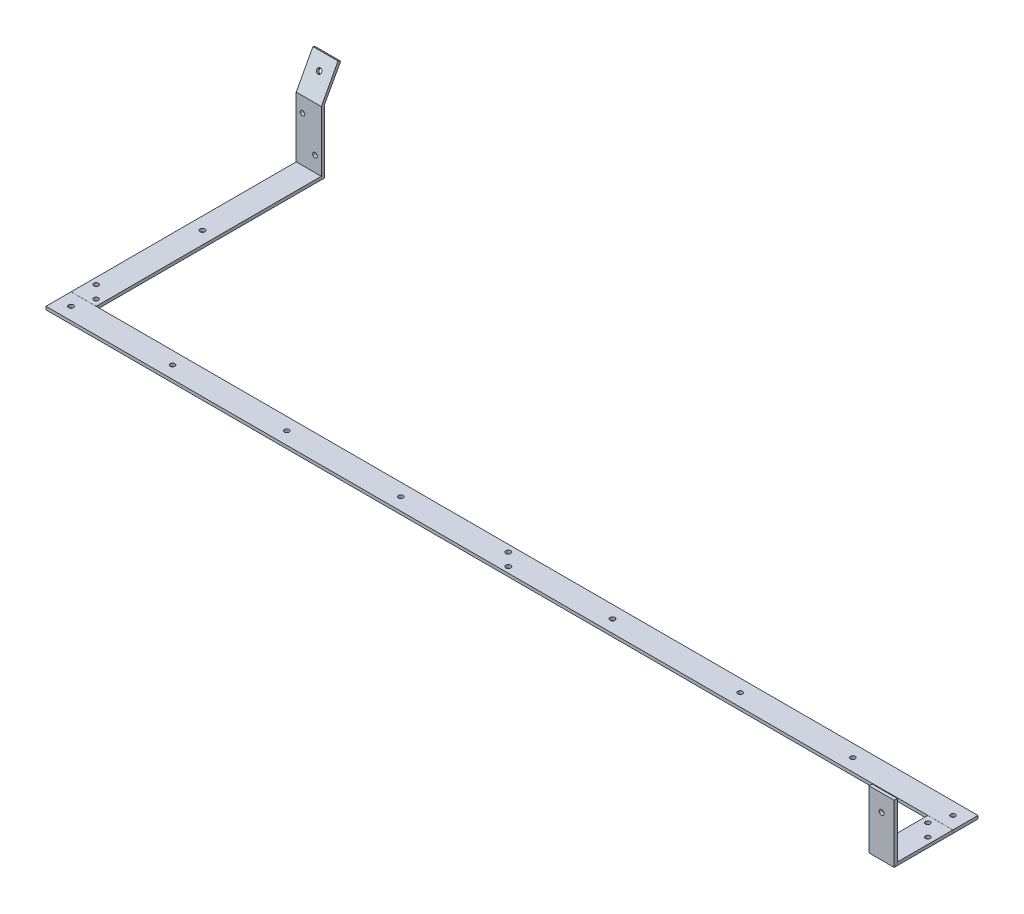
SolidWorks part; units mm, degrees
ref_plane "Alzado" through (0, 0, 0) normal (0, 0, 1) x (1, 0, 0)
ref_plane "Planta" through (0, 0, 0) normal (0, 1, 0) x (1, 0, 0)
ref_plane "Vista lateral" through (0, 0, 0) normal (1, 0, 0) x (0, 0, -1)
sketch "Croquis2" plane through (0, 0, 0) normal (0, 0, 1) x (1, 0, 0)
  line L1 (-25.4, 64.345) -> (25.4, 64.345)
  line L2 (-25.4, 64.345) -> (-25.4, -64.345)
  line L3 (-25.4, -64.345) -> (25.4, -64.345)
  line L4 (25.4, 64.345) -> (25.4, -64.345)
  line L5 (-25.4, 64.345) -> (25.4, -64.345) construction
  line L6 (-25.4, -64.345) -> (25.4, 64.345) construction
  point P0 (0, 0)
  dimension "D1" = 128.69
  dimension "D2" = 50.8
extrude "Saliente-Extruir1" add sketch "Croquis2" along normal blind 6.31
sketch "Croquis3" plane through (0, 0, 6.31) normal (0, 0, 1) x (1, 0, 0)
  line L1 (-25.4, -58.035) -> (25.4, -58.035)
  line L2 (-25.4, -58.035) -> (-25.4, -64.345)
  line L3 (-25.4, -64.345) -> (25.4, -64.345)
  line L4 (25.4, -58.035) -> (25.4, -64.345)
  line L5 (-25.4, -58.035) -> (25.4, -64.345) construction
  line L6 (-25.4, -64.345) -> (25.4, -58.035) construction
  point P0 (0, -61.19)
  dimension "D1" = 6.31
  dimension "D2" = 50.8
extrude "Saliente-Extruir2" add sketch "Croquis3" along normal blind 507.13
sketch "Croquis4" plane through (25.4, 0, 0) normal (1, 0, 0) x (0, 0, -1)
  line L1 (-462.64, -64.345) -> (-513.44, -64.345)
  line L2 (-462.64, -64.345) -> (-462.64, -58.035)
  line L3 (-462.64, -58.035) -> (-513.44, -58.035)
  line L4 (-513.44, -64.345) -> (-513.44, -58.035)
  line L5 (-462.64, -64.345) -> (-513.44, -58.035) construction
  line L6 (-462.64, -58.035) -> (-513.44, -64.345) construction
  point P0 (-488.04, -61.19)
  dimension "D1" = 50.8
extrude "Saliente-Extruir3" add sketch "Croquis4" along normal blind 1787.3
sketch "Croquis9" plane through (0, 0, 513.44) normal (0, 0, 1) x (1, 0, 0)
  line L0 (1812.7, -58.035) -> (-25.4, -58.035) construction
  line L1 (1761.9, -58.035) -> (1812.7, -58.035)
  line L2 (1761.9, -58.035) -> (1761.9, -64.345)
  line L3 (1761.9, -64.345) -> (1812.7, -64.345)
  line L4 (1812.7, -58.035) -> (1812.7, -64.345)
  line L5 (1761.9, -58.035) -> (1812.7, -64.345) construction
  line L6 (1761.9, -64.345) -> (1812.7, -58.035) construction
  point P0 (1787.3, -61.19)
  dimension "D1" = 50.8
sketch3d "Croquis3D3"
  line L0 (1787.3, -61.19, 513.44) -> (1787.3, -61.19, 629.44)
  line L1 (1787.3, -61.19, 629.44) -> (1787.3, 63.52, 629.44)
  line L2 (1787.3, 63.52, 629.44) -> (1787.3, 63.52, 1423.44)
  dimension "D1" = 116
  dimension "D2" = 124.71
  dimension "D3" = 794
sweep "Barrer2" add profiles "Croquis9" path "Croquis3D3"
sketch "Croquis11" plane through (-25.4, 0, 0) normal (-1, 0, 0) x (0, 0, 1)
  line L0 (0, 64.345) -> (-33.0683, 124.3223)
  line L1 (-33.0683, 124.3223) -> (-27.5425, 127.369)
  line L2 (-27.5425, 127.369) -> (6.31, 64.345)
  line L3 (0, 64.345) -> (6.31, 64.345)
  line L4 (0, 64.345) -> (0, -64.345) construction
  dimension "D1" = 6.31
  dimension "D2" = 151.13
  dimension "D3" = 71.5403
extrude "Saliente-Extruir4" add sketch "Croquis11" against normal blind 98
sketch "Croquis12" plane through (0, 66.675, 0) normal (0, 1, 0) x (1, 0, 0)
  line L0 (1787.3, -1423.44) -> (1787.3, -1390.44) construction
  line L1 (1787.3, -629.44) -> (1787.3, -1423.44) construction
  line L2 (1787.3, -1390.44) -> (1787.3, -1170.44) construction
  circle A0 centre (1787.3, -1390.44) radius 5
  circle A1 centre (1787.3, -1170.44) radius 5
  dimension "D3" = 10
  dimension "D4" = 10
  dimension "D1" = 33
  dimension "D2" = 220
extrude "Cortar-Extruir1" cut sketch "Croquis12" against normal blind 10
sketch "Croquis13" plane through (1812.7, 0, 0) normal (1, 0, 0) x (0, 0, -1)
  line L0 (-632.595, 53.5613) -> (-626.285, 53.5613)
  line L1 (-632.595, -64.345) -> (-632.595, 60.365) construction
  line L2 (-626.285, -58.035) -> (-626.285, 66.675) construction
  line L3 (-626.285, 53.5613) -> (-626.285, 66.675)
  line L4 (-626.285, 66.675) -> (-1423.44, 66.675)
  line L5 (-1423.44, 66.675) -> (-1423.44, 60.365)
  line L6 (-1423.44, 60.365) -> (-632.595, 60.365)
  line L7 (-632.595, 60.365) -> (-632.595, 53.5613)
  dimension "D1" = 13.1137
extrude "Cortar-Extruir2" cut sketch "Croquis13" against normal blind 73
sketch "Croquis16" plane through (0, 17.0382, 31.7203) normal (0, 0.4732, 0.881) x (1, 0, 0)
  line L0 (25.4, 53.6994) -> (25.4, 125.2397)
  line L1 (72.6, 125.2397) -> (-25.4, 125.2397) construction
  line L2 (25.4, 125.2397) -> (72.6, 125.2397)
  line L3 (72.6, 125.2397) -> (72.6, 53.6994)
  line L4 (72.6, 53.6994) -> (25.4, 53.6994)
extrude "Cortar-Extruir5" cut sketch "Croquis16" against normal blind 10
sketch "Croquis21" plane through (0, -58.035, 0) normal (0, 1, 0) x (1, 0, 0)
  line L0 (0, -216.8772) -> (0, -221.6422) construction
  line L1 (0, -221.6422) -> (0, -244.6422) construction
  line L2 (0, -244.6422) -> (0, -198.6422) construction
  circle A0 centre (0, -221.6422) radius 4.765 construction
  circle A1 centre (0, -221.6422) radius 5
  circle A2 centre (0, -244.6422) radius 3.5 construction
  circle A3 centre (0, -198.6422) radius 3.5 construction
  dimension "D1" = 10
  dimension "D2" = 7
  dimension "D3" = 7
extrude "Cortar-Extruir11" cut sketch "Croquis21" against normal blind 10
sketch "Croquis24" plane through (0, -58.035, 0) normal (0, 1, 0) x (1, 0, 0)
  line L0 (25.4, -462.64) -> (-25.4, -462.64)
  line L1 (-25.4, -513.44) -> (-25.4, -6.31) construction
  line L2 (-25.4, -462.64) -> (-25.4, -462.54)
  line L3 (-25.4, -462.54) -> (25.4, -462.54)
  line L4 (25.4, -462.64) -> (25.4, -6.31) construction
  line L5 (25.4, -462.54) -> (25.4, -462.64)
  dimension "D1" = 0.1
sketch "Croquis25" plane through (0, -58.035, 0) normal (0, 1, 0) x (1, 0, 0)
  line L0 (1761.9, -513.44) -> (1812.7, -513.44)
  line L1 (1812.7, -462.64) -> (1812.7, -626.285) construction
  line L2 (1812.7, -513.44) -> (1812.7, -513.54)
  line L3 (1812.7, -513.54) -> (1761.9, -513.54)
  line L4 (1761.9, -513.44) -> (1761.9, -626.285) construction
  line L5 (1761.9, -513.54) -> (1761.9, -513.44)
  dimension "D1" = 0.1
extrude "Cortar-Extruir14" cut sketch "Croquis25" against normal blind 50.8
extrude "Cortar-Extruir15" cut sketch "Croquis24" against normal blind 50.8
sketch "Croquis26" plane through (0, -58.035, 0) normal (0, 1, 0) x (1, 0, 0)
  line L0 (1812.7, -488.04) -> (1761.9, -488.04) construction
  line L1 (1812.7, -462.64) -> (1812.7, -513.44) construction
  line L2 (1761.9, -488.04) -> (1787.3, -488.04) construction
  line L3 (1787.3, -488.04) -> (1787.3, -477.1303) construction
  line L4 (1787.3, -477.1303) -> (1774.6, -440.5449) construction
  circle A0 centre (1787.3, -488.04) radius 4.7625
  dimension "D1" = 9.525
extrude "Cortar-Extruir16" cut sketch "Croquis26" against normal blind 33
sketch "Croquis27" plane through (0, 0, 626.285) normal (0, 0, -1) x (-1, 0, 0)
  line L0 (-1787.3, 53.5613) -> (-1787.3, 19.5613) construction
  line L1 (-1761.9, 53.5613) -> (-1812.7, 53.5613) construction
  line L2 (-1787.3, -61.19) -> (-1787.3, 63.52) construction
  circle A0 centre (-1787.3, 19.5613) radius 5
  dimension "D2" = 10
  dimension "D1" = 34
extrude "Cortar-Extruir17" cut sketch "Croquis27" against normal blind 33
sketch "Croquis28" plane through (0, -64.345, 0) normal (0, -1, 0) x (-1, 0, 0)
  circle A0 centre (-900, -501.935) radius 5
  circle A1 centre (-874.6, -476.535) radius 5
extrude "Cortar-Extruir18" cut sketch "Croquis28" against normal blind 10
sketch "Croquis29" plane through (0, -64.345, 0) normal (0, -1, 0) x (-1, 0, 0)
  circle A0 centre (12.7, -424.54) radius 4.7625
  circle A1 centre (-12.7, -449.94) radius 4.7625
extrude "Cortar-Extruir19" cut sketch "Croquis29" against normal blind 10
sketch "Croquis30" plane through (0, -64.345, 0) normal (0, -1, 0) x (-1, 0, 0)
  circle A0 centre (-1800, -551.54) radius 4.7625
  circle A1 centre (-1774.6, -526.14) radius 4.7625
extrude "Cortar-Extruir20" cut sketch "Croquis30" against normal blind 50
sketch "Croquis31" plane through (0, -64.345, 0) normal (0, -1, 0) x (-1, 0, 0)
  line L0 (-1097.3, -493.04) -> (-1097.3, -488.04) construction
  line L1 (-1097.3, -488.04) -> (-1102.3, -488.04) construction
  circle A0 centre (-1097.3, -488.04) radius 5 construction
  circle A1 centre (-1097.3, -488.04) radius 5
extrude "Cortar-Extruir21" cut sketch "Croquis31" against normal blind 50
sketch "Croquis32" plane through (0, -58.035, 0) normal (0, 1, 0) x (1, 0, 0)
  line L0 (-25.4, -488.04) -> (25.4, -488.04) construction
  line L1 (-25.4, -513.44) -> (-25.4, -462.64) construction
  line L2 (25.4, -488.04) -> (0, -488.04) construction
  line L3 (0, -488.04) -> (0, -513.44) construction
  line L4 (1812.7, -513.44) -> (-25.4, -513.44) construction
  circle A0 centre (0, -488.04) radius 5
  dimension "D1" = 10
extrude "Cortar-Extruir22" cut sketch "Croquis32" against normal blind 50
sketch "Croquis33" plane through (0, 17.0382, 31.7203) normal (0, 0.4732, 0.881) x (1, 0, 0)
  line L0 (0, 125.2397) -> (0, 98.1197) construction
  line L1 (25.4, 125.2397) -> (-25.4, 125.2397) construction
  circle A0 centre (0, 98.1197) radius 5
  dimension "D2" = 10
  dimension "D1" = 27.12
extrude "Cortar-Extruir23" cut sketch "Croquis33" against normal blind 50
sketch "Croquis34" plane through (0, 0, 6.31) normal (0, 0, 1) x (1, 0, 0)
  line L0 (-25.4, 64.345) -> (-25.4, -58.035) construction
  line L1 (-25.4, -58.035) -> (-25.4, 3.155) construction
  line L2 (-25.4, 3.155) -> (25.4, 3.155) construction
  line L3 (25.4, -58.035) -> (25.4, 64.345) construction
  line L4 (-25.4, 3.155) -> (-25.4, -58.035) construction
  line L5 (-25.4, -58.035) -> (-25.4, -27.44) construction
  line L6 (-25.4, -27.44) -> (0, -27.44) construction
  line L7 (0, -27.44) -> (-12.7, -27.44) construction
  line L8 (0, -27.44) -> (25.4, -27.44) construction
  line L9 (25.4, -27.44) -> (12.7, -27.44) construction
  line L10 (0, 33.75) -> (-12.7, 33.75) construction
  circle A0 centre (-12.7, -27.44) radius 4.7625 construction
  circle A1 centre (12.7, -27.44) radius 4.765
  circle A2 centre (12.7, 33.75) radius 4.765 construction
  circle A3 centre (-12.7, 33.75) radius 4.7625
  dimension "D1" = 9.525
  dimension "D2" = 9.53
extrude "Cortar-Extruir24" cut sketch "Croquis34" against normal blind 10
sketch "Croquis35" plane through (0, -58.035, 0) normal (0, 1, 0) x (1, 0, 0)
  line L0 (1812.7, -488.04) -> (-25.4, -488.04) construction
  line L1 (1812.7, -462.64) -> (1812.7, -513.44) construction
  line L2 (-25.4, -513.44) -> (-25.4, -462.64) construction
  line L3 (-25.4, -488.04) -> (899.5757, -488.04) construction
  line L4 (899.5757, -488.04) -> (437.0879, -488.04) construction
  line L5 (437.0879, -488.04) -> (668.3318, -488.04) construction
  line L6 (437.0879, -488.04) -> (-25.4, -488.04) construction
  line L7 (-25.4, -488.04) -> (205.8439, -488.04) construction
  line L8 (899.5757, -488.04) -> (1812.7, -488.04) construction
  line L9 (1812.7, -488.04) -> (1356.1379, -488.04) construction
  line L10 (1356.1379, -488.04) -> (1584.4189, -488.04) construction
  circle A0 centre (1584.4189, -488.04) radius 4.765
  circle A1 centre (1356.1379, -488.04) radius 4.765
  circle A2 centre (668.3318, -488.04) radius 4.765
  circle A3 centre (437.0879, -488.04) radius 4.765
  circle A4 centre (205.8439, -488.04) radius 4.7625
  dimension "D1" = 9.525
  dimension "D2" = 9.53
  dimension "D3" = 9.53
  dimension "D4" = 9.53
  dimension "D5" = 9.53
extrude "Cortar-Extruir25" cut sketch "Croquis35" against normal blind 10
